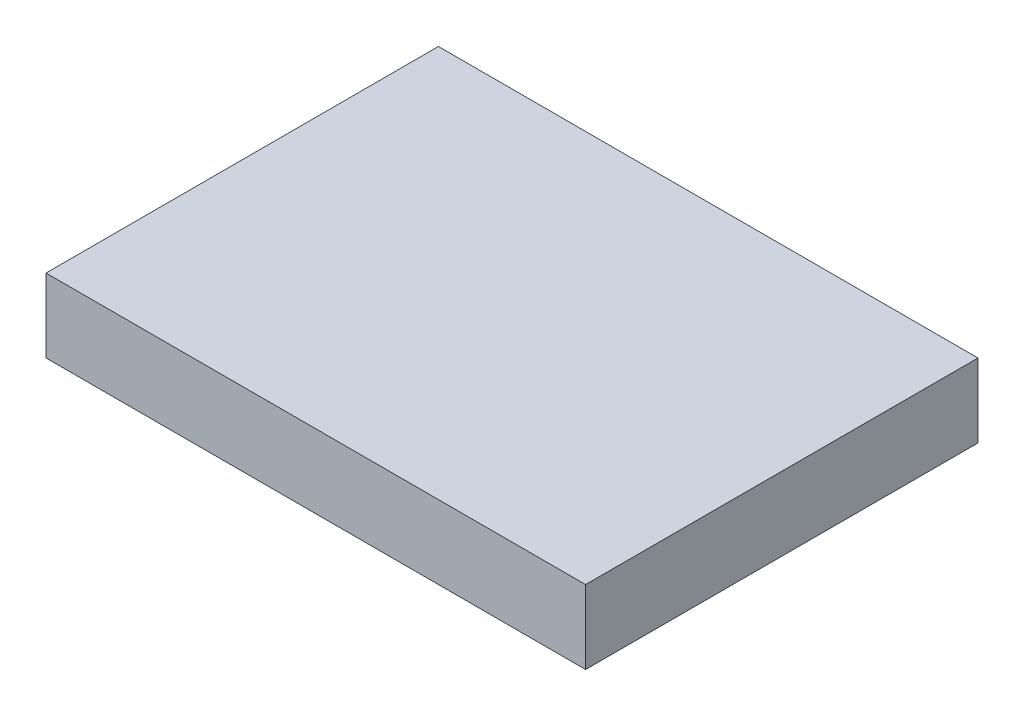
SolidWorks part; units mm, degrees
ref_plane "Front Plane" through (0, 0, 0) normal (0, 0, 1) x (1, 0, 0)
ref_plane "Top Plane" through (0, 0, 0) normal (0, 1, 0) x (1, 0, 0)
ref_plane "Right Plane" through (0, 0, 0) normal (1, 0, 0) x (0, 0, -1)
sketch "Sketch1" plane through (0, 0, 0) normal (0, 1, 0) x (1, 0, 0)
  line L1 (0, 0) -> (69.85, 0)
  line L2 (0, 0) -> (0, 50.8)
  line L3 (0, 50.8) -> (69.85, 50.8)
  line L4 (69.85, 0) -> (69.85, 50.8)
  dimension "D1" = 69.85
  dimension "D2" = 50.8
extrude "Boss-Extrude1" add sketch "Sketch1" along normal blind 9.525
